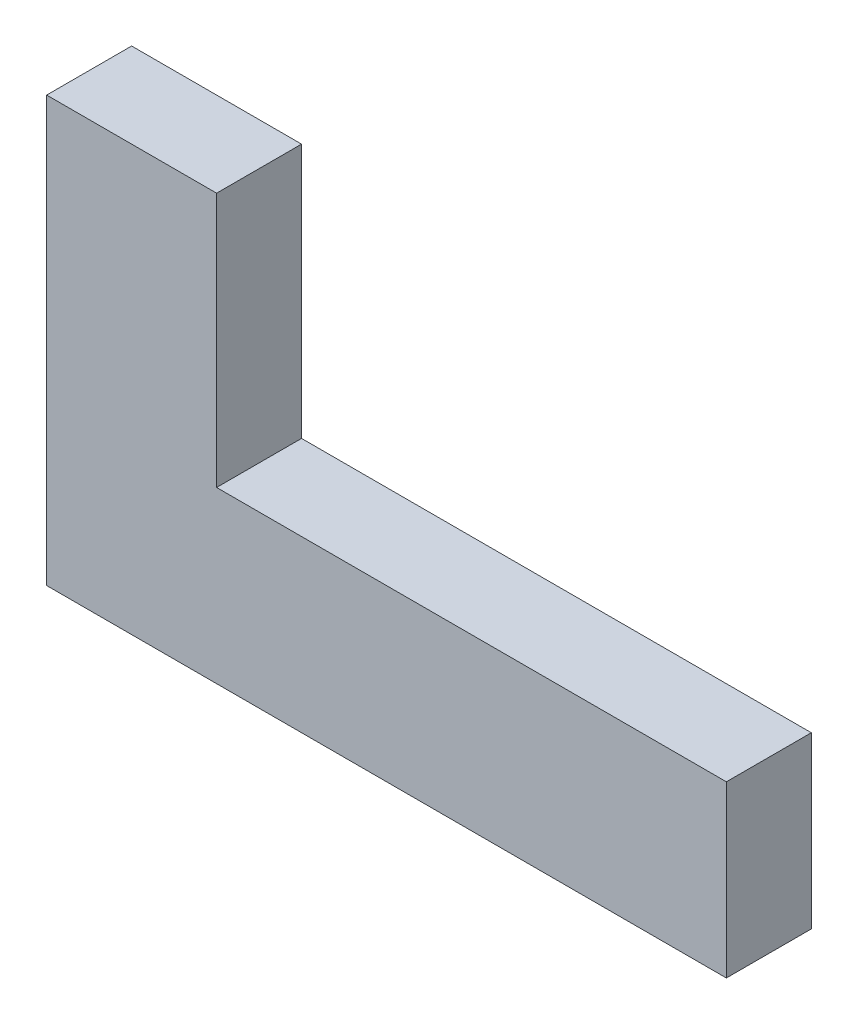
SolidWorks part; units mm, degrees
ref_plane "Front Plane" through (0, 0, 0) normal (0, 0, 1) x (1, 0, 0)
ref_plane "Top Plane" through (0, 0, 0) normal (0, 1, 0) x (1, 0, 0)
ref_plane "Right Plane" through (0, 0, 0) normal (1, 0, 0) x (0, 0, -1)
sketch "Sketch1" plane through (0, 0, 0) normal (0, 0, 1) x (1, 0, 0)
  line L0 (-53.0709, 38.878) -> (-53.0709, -11.122)
  line L1 (-53.0709, 38.878) -> (-33.0709, 38.878)
  line L2 (-33.0709, 38.878) -> (-33.0709, 8.878)
  line L3 (-33.0709, 8.878) -> (26.9291, 8.878)
  line L4 (26.9291, 8.878) -> (26.9291, -11.122)
  line L5 (26.9291, -11.122) -> (-53.0709, -11.122)
  dimension "D1" = 50
  dimension "D2" = 20
  dimension "D3" = 20
  dimension "D4" = 80
extrude "Boss-Extrude1" add sketch "Sketch1" along normal blind 10
